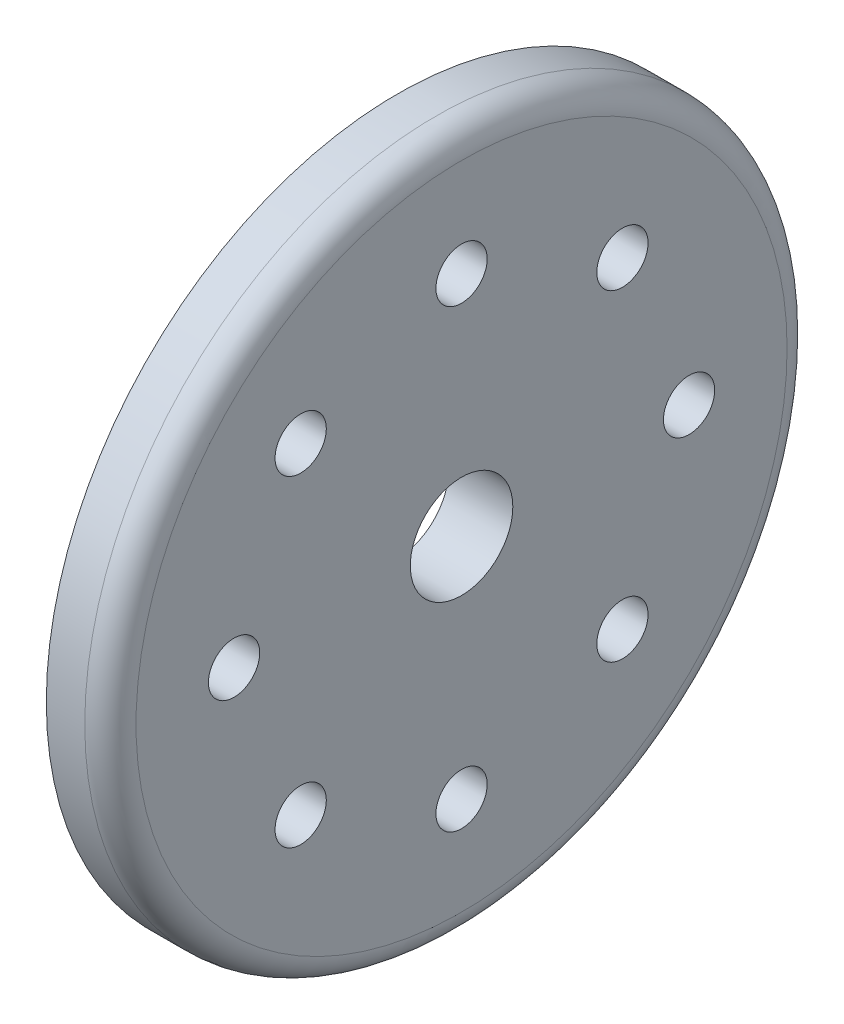
SolidWorks part; units mm, degrees
ref_plane "Front Plane" through (0, 0, 0) normal (0, 0, 1) x (1, 0, 0)
ref_plane "Top Plane" through (0, 0, 0) normal (0, 1, 0) x (1, 0, 0)
ref_plane "Right Plane" through (0, 0, 0) normal (1, 0, 0) x (0, 0, -1)
sketch "Sketch1" plane through (0, 0, 0) normal (1, 0, 0) x (0, 0, -1)
  circle A0 centre (0, 0) radius 34.798
extrude "Boss-Extrude1" add sketch "Sketch1" along normal blind 6.35
fillet "Fillet1" radius 2.54 1 edges at (6.35, 0, -34.798)
sketch "Sketch2" plane through (6.35, 0, 0) normal (1, 0, 0) x (0, 0, -1)
  circle A0 centre (0, 0) radius 5.08
extrude "Cut-Extrude1" cut sketch "Sketch2" against normal blind 6.35
sketch "Sketch3" plane through (6.35, 0, 0) normal (1, 0, 0) x (0, 0, -1)
  circle A0 centre (22.5439, 0) radius 2.54
extrude "Cut-Extrude2" cut sketch "Sketch3" against normal blind 19.05
pattern_circular "CirPattern1" count 8 over 360 about axis through (0, 0, 0) along (1, 0, 0) of "Cut-Extrude2"
